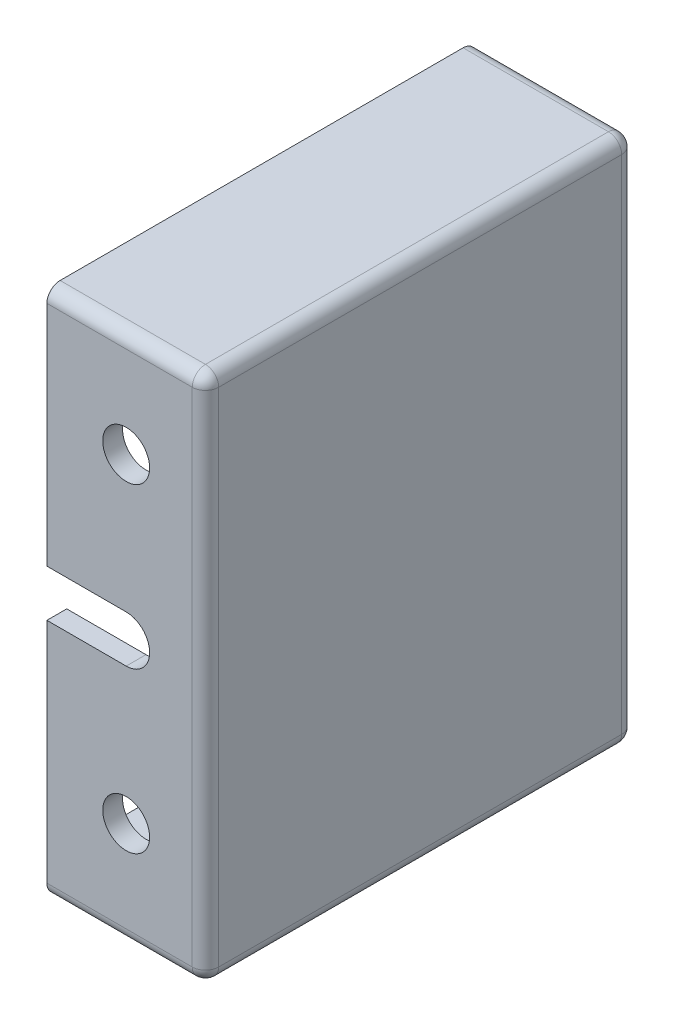
SolidWorks part; units mm, degrees
ref_plane "Front Plane" through (0, 0, 0) normal (1, 0, 0) x (0, 1, 0)
ref_plane "Top Plane" through (0, 0, 0) normal (0, 0, 1) x (0, 1, 0)
ref_plane "Right Plane" through (0, 0, 0) normal (0, 1, 0) x (-1, 0, 0)
sketch "Sketch1" plane through (0, 0, 0) normal (0, 0, 1) x (0, 1, 0)
  line L1 (-40, -12) -> (40, -12)
  line L2 (-40, -12) -> (-40, 12)
  line L3 (-40, 12) -> (40, 12)
  line L4 (40, -12) -> (40, 12)
  line L5 (-40, -12) -> (40, 12) construction
  line L6 (-40, 12) -> (40, -12) construction
  line L7 (0, 12) -> (0, -12) construction
  circle A0 centre (0, 0) radius 3
  point P0 (0, 0)
  dimension "D3" = 6
  dimension "D1" = 24
  dimension "D2" = 80
extrude "Boss-Extrude1" add sketch "Sketch1" along normal blind 65
shell "2 mm top/bot 3 mm side" thickness 3
sketch "Sketch3" plane through (0, 0, 0) normal (0, 0, -1) x (1, 0, 0)
  line L0 (0, 40) -> (0, -40) construction
  line L1 (12, 40) -> (-12, 40) construction
  line L2 (12, -40) -> (-12, -40) construction
  line L3 (0, 40) -> (0, 27.4)
  line L4 (0, -40) -> (0, -27.4)
  circle A0 centre (0, 22.5) radius 4.9
  circle A1 centre (0, 7.5) radius 4.9
  circle A2 centre (0, -7.5) radius 4.9
  circle A3 centre (0, -22.5) radius 4.9
  dimension "D1" = 9.8
  dimension "D2" = 4
extrude "9.8 mm port holes" cut sketch "Sketch3" against normal up to surface (3 mm away) contours L0 A0 | A0 L0 | A1 L0 | L0 A1 | A2 L0 | L0 A2 | L0 A3 | A3 L0 up to face at (-1.5, 0, 3)
sketch "Sketch4" plane through (0, 0, 65) normal (0, 0, 1) x (1, 0, 0)
  line L0 (0, 40) -> (0, -40) construction
  line L1 (12, 40) -> (-12, 40) construction
  line L2 (12, -40) -> (-12, -40) construction
  line L3 (0, 3.55) -> (0, 20.65)
  line L4 (-12, 0) -> (12, 0) construction
  line L5 (-12, -40) -> (-12, 40) construction
  line L6 (12, -40) -> (12, 40) construction
  line L7 (0, 3.55) -> (-12, 3.55)
  line L8 (0, -3.55) -> (-12, -3.55)
  line L9 (-12, -3.55) -> (-12, 3.55)
  circle A0 centre (0, 0) radius 3.55
  circle A1 centre (0, 24.2) radius 3.55
  circle A2 centre (0, -24.2) radius 3.55
  line M6 (-12, 40) -> (-12, -40)
  dimension "D1" = 7.1
  dimension "D2" = 17.1
extrude "7.1 mm fixture holes" cut sketch "Sketch4" along direction (0, 0, 1) on the side against the normal blind 10 contours A1 | A0 | A2 | A0 L7 L8 M6
fillet "2 mm radius" radius 2 4 edges at (9, 35, 32.5) (9, -35, 32.5) (12, -40, 32.5) (12, 40, 32.5)
sketch "Sketch7" plane through (0, 40, 0) normal (0, 1, 0) x (-1, 0, 0)
  line L0 (1, 65) -> (1, 0) construction
  line L1 (-10, 65) -> (12, 65) construction
  line L2 (-10, 0) -> (12, 0) construction
  circle A0 centre (1, 32.5) radius 4.25
  dimension "D1" = 8.5
extrude "8.5 mm hold offset 2 mm" cut sketch "Sketch7" against normal blind 3.2 from offset 2 offset against normal yes
mirror "magnet slot mirror" about plane through (0, 0, 0) normal (0, 1, 0) of "8.5 mm hold offset 2 mm"
fillet "R2 filet" radius 2 20 edges at (8.4142, -34.4142, 62) (9, 0, 62) (8.4142, 34.4142, 62) (8.4142, -34.4142, 3) (9, 0, 3) (8.4142, 34.4142, 3) (-2.5, -35, 62) (-2.5, 35, 62) (-2.5, -35, 3) (-2.5, 35, 3) (-1, -40, 65) (11.4142, -39.4142, 65) (12, 0, 65) (11.4142, 39.4142, 65) (-1, 40, 0) (11.4142, 39.4142, 0) (12, 0, 0) (11.4142, -39.4142, 0) (-1, 40, 65) (-1, -40, 0)
sketch "Sketch8" plane through (-12, 0, 0) normal (-1, 0, 0) x (0, -1, 0)
  line L0 (-35, 5) -> (-35, 60) construction
  line L1 (-36.5, 31) -> (-33.5, 31)
  line L2 (-36.5, 31) -> (-36.5, 34)
  line L3 (-36.5, 34) -> (-33.5, 34)
  line L4 (-33.5, 31) -> (-33.5, 34)
  line L5 (-36.5, 31) -> (-33.5, 34) construction
  line L6 (-36.5, 34) -> (-33.5, 31) construction
  point P0 (-35, 32.5)
  dimension "D1" = 3
extrude "7 mm notch" cut sketch "Sketch8" against normal blind 7
mirror "7 mm notch mirror" about plane through (0, 0, 0) normal (0, 1, 0) of "7 mm notch"
